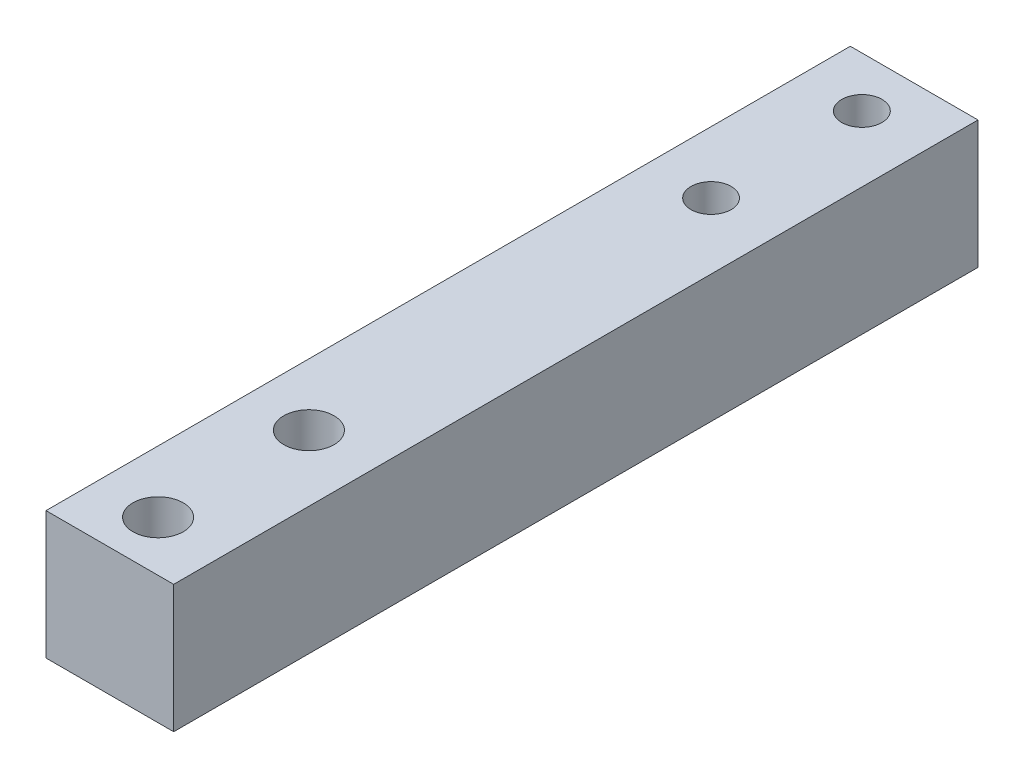
SolidWorks part; units mm, degrees
ref_plane "Płaszczyzna przednia" through (0, 0, 0) normal (0, 0, 1) x (1, 0, 0)
ref_plane "Płaszczyzna górna" through (0, 0, 0) normal (0, 1, 0) x (1, 0, 0)
ref_plane "Płaszczyzna prawa" through (0, 0, 0) normal (1, 0, 0) x (0, 0, -1)
sketch "Szkic1" plane through (0, -32.274, 0) normal (0, 1, 0) x (1, 0, 0)
  line L0 (-262.4422, 48.1575) -> (-262.4422, 128.1575)
  line L1 (-262.4422, 48.1575) -> (-275.1422, 48.1575)
  line L2 (-262.4422, 128.1575) -> (-275.1422, 128.1575)
  line L3 (-275.1422, 48.1575) -> (-275.1422, 128.1575)
  dimension "D1" = 12.7
  dimension "D2" = 80
extrude "Dodanie-wyciągnięcie1" add sketch "Szkic1" against normal blind 12.7
sketch "Szkic2" plane through (0, -44.974, 0) normal (0, -1, 0) x (-1, 0, 0)
  line L3 (262.4422, 128.1575) -> (275.1422, 128.1575) construction
  line L4 (275.1422, 48.1575) -> (262.4422, 48.1575) construction
  circle A0 centre (268.9926, 123.1575) radius 2
  circle A1 centre (268.9926, 108.1575) radius 2
  circle A2 centre (268.9926, 53.1575) radius 2.5
  circle A3 centre (268.9926, 68.1575) radius 2.5
  dimension "D1" = 5
  dimension "D2" = 15
  dimension "D3" = 15
  dimension "D4" = 5
  dimension "D5" = 5
  dimension "D6" = 5
  dimension "D7" = 4
  dimension "D8" = 4
extrude "Wytnij-wyciągnięcie1" cut sketch "Szkic2" against normal blind 12.7
